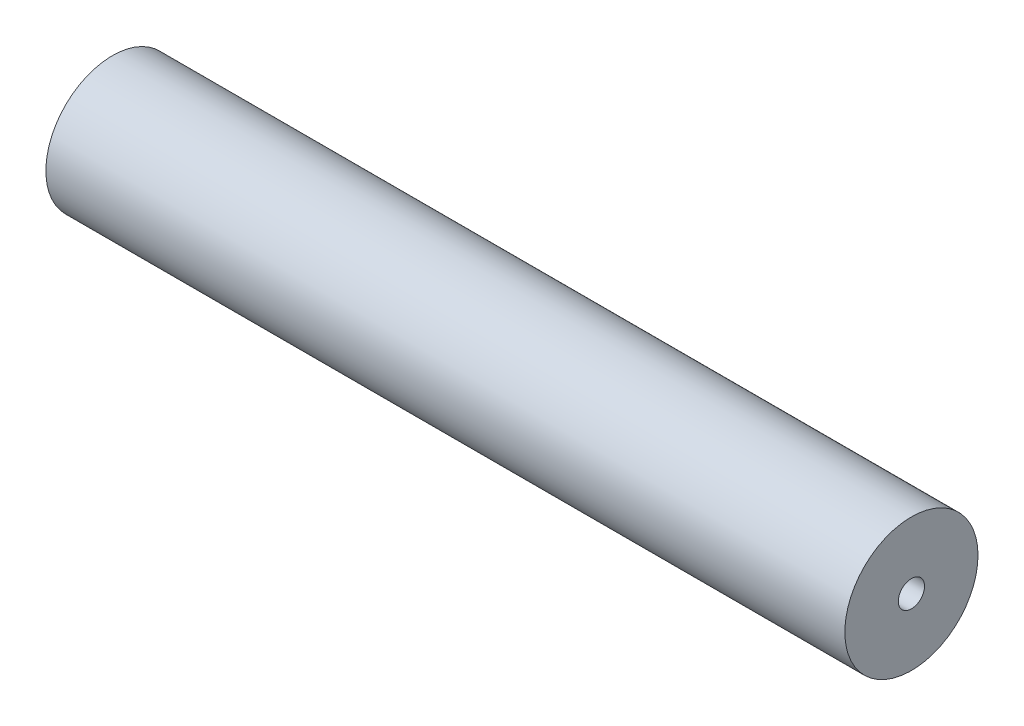
SolidWorks part; units mm, degrees
material "AISI 1020"
ref_plane "Front Plane" through (0, 0, 0) normal (0, 0, 1) x (1, 0, 0)
ref_plane "Top Plane" through (0, 0, 0) normal (0, 1, 0) x (1, 0, 0)
ref_plane "Right Plane" through (0, 0, 0) normal (1, 0, 0) x (0, 0, -1)
sketch "Sketch1" plane through (0, 0, 0) normal (1, 0, 0) x (0, 0, -1)
  circle A0 centre (0, 0) radius 38.1
  dimension "D1" = 76.2
extrude "Boss-Extrude1" add sketch "Sketch1" along normal blind 457.2
sketch "Sketch3" plane through (0, 0, 0) normal (-1, 0, 0) x (0, 0, 1)
  circle A0 centre (0, 0) radius 12.7
  dimension "D1" = 25.4
hole_wizard "M12 Clearance Hole1" positions "Sketch4" profile "Sketch5" hole size "M12" standard "ANSI Metric"
sketch "Sketch4" plane through (0, 0, 0) normal (-1, 0, 0) x (0, 0, 1)
  point P0 (0, 0)
sketch "Sketch5" plane through (0, 0, 0) normal (0, 1, 0) x (0, 0, 1)
  line L0 (0, 0) -> (0, 25.4)
  line L1 (0, 25.4) -> (6.75, 21.3442)
  line L2 (6.75, 21.3442) -> (6.75, 0.025)
  line L3 (6.75, 0.025) -> (6.775, 0)
  line L5 (6.775, 0) -> (0, 0)
  line L6 (-6.75, 0.025) -> (-6.775, 0) construction
  line L10 (0, 25.4) -> (-6.75, 21.3442) construction
  line L11 (0, -6.35) -> (0, 107.95) construction
  dimension "Hole Dia." = 13.5
  dimension "Hole Depth" = 25.4
  dimension "Near C'Sink Dia." = 13.55
  dimension "Near C'Sink Angle" = 90
  dimension "Drill Angle" = 118
hole_wizard "M12 Clearance Hole2" positions "Sketch8" profile "Sketch9" hole size "M12" standard "ANSI Metric"
sketch "Sketch8" plane through (457.2, 0, 0) normal (1, 0, 0) x (0, 0, -1)
  point P0 (0, 0)
sketch "Sketch9" plane through (457.2, 0, 0) normal (0, 1, 0) x (0, 0, -1)
  line L0 (0, 0) -> (0, 25.4)
  line L1 (0, 25.4) -> (7.5, 20.8935)
  line L2 (7.5, 20.8935) -> (7.5, 0)
  line L5 (7.5, 0) -> (0, 0)
  line L10 (0, 25.4) -> (-7.5, 20.8935) construction
  line L11 (0, -6.35) -> (0, 107.95) construction
  dimension "Hole Dia." = 15
  dimension "Hole Depth" = 25.4
  dimension "Drill Angle" = 118
